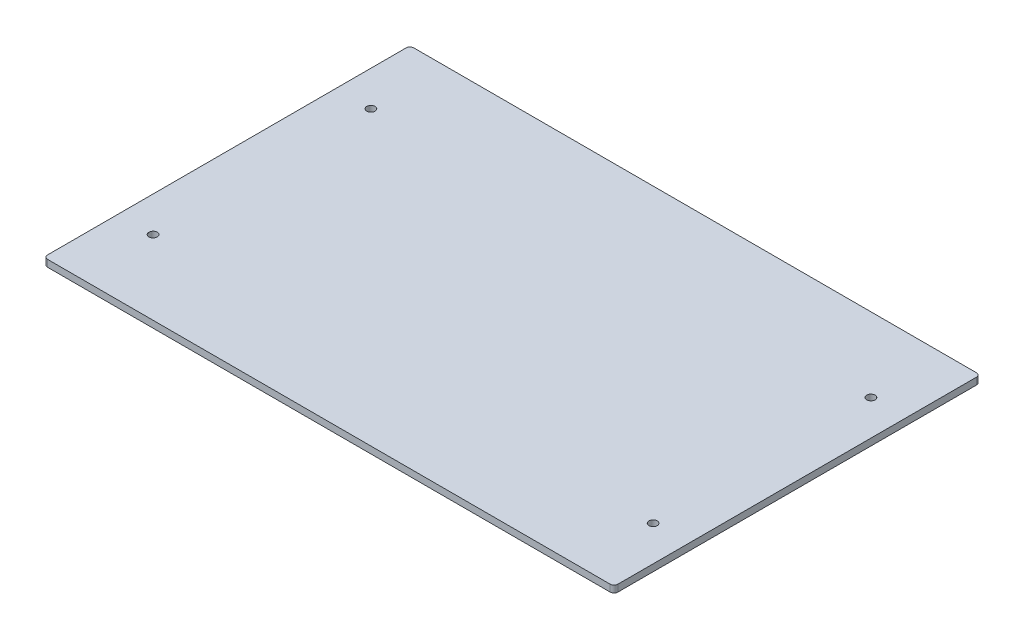
SolidWorks part; units mm, degrees
material "ABS PC"
ref_plane "Front Plane" through (0, 0, 0) normal (0, 0, 1) x (1, 0, 0)
ref_plane "Top Plane" through (0, 0, 0) normal (0, 1, 0) x (1, 0, 0)
ref_plane "Right Plane" through (0, 0, 0) normal (1, 0, 0) x (0, 0, -1)
sketch "Sketch1" plane through (0, 0, 0) normal (0, 1, 0) x (1, 0, 0)
  line L0 (231.775, 297.688) -> (231.775, 0) construction
  line L1 (0, 0) -> (463.55, 0)
  line L2 (0, 0) -> (0, 297.688)
  line L3 (0, 297.688) -> (463.55, 297.688)
  line L4 (463.55, 0) -> (463.55, 297.688)
  line L5 (28.575, 60.325) -> (28.575, 237.363) construction
  line L6 (28.575, 237.363) -> (28.575, 414.401) construction
  line L7 (434.975, 237.363) -> (434.975, 414.401) construction
  line L8 (434.975, 60.325) -> (434.975, 237.363) construction
  circle A0 centre (28.575, 60.325) radius 3.3782
  circle A1 centre (28.575, 237.363) radius 3.3782
  circle A4 centre (434.975, 237.363) radius 3.3782
  circle A5 centre (434.975, 60.325) radius 3.3782
  dimension "D3" = 6.7564
  dimension "D1" = 463.55
  dimension "D2" = 60.325
  dimension "D4" = 60.325
  dimension "D5" = 28.575
  dimension "D6" = 177.038
extrude "Boss-Extrude1" add sketch "Sketch1" along normal blind 5.588
fillet "Fillet1" radius 3.175 4 edges at (0, 2.794, -297.688) (463.55, 2.794, -297.688) (0, 2.794, 0) (463.55, 2.794, 0)
